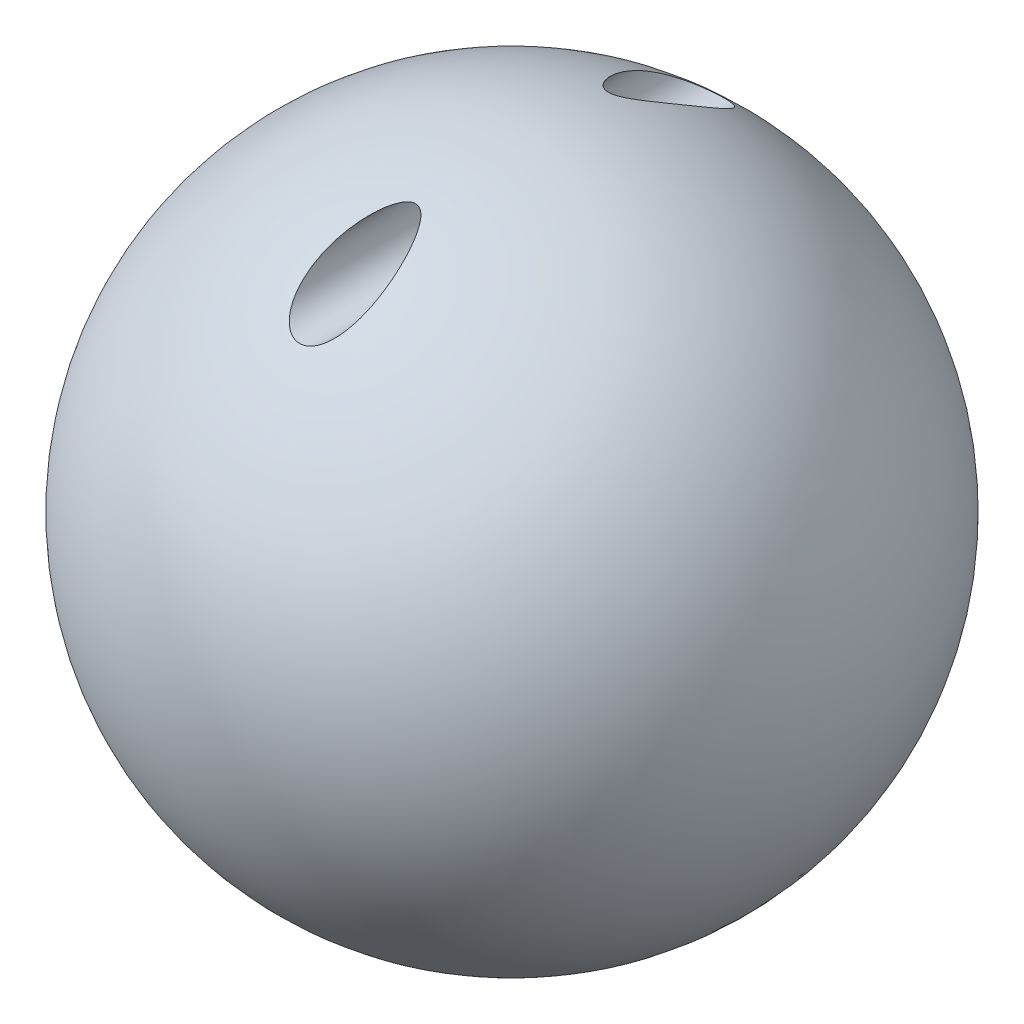
SolidWorks part; units mm, degrees
ref_plane "Front Plane" through (0, 0, 0) normal (0, 0, 1) x (1, 0, 0)
ref_plane "Top Plane" through (0, 0, 0) normal (0, 1, 0) x (1, 0, 0)
ref_plane "Right Plane" through (0, 0, 0) normal (1, 0, 0) x (0, 0, -1)
sketch "Sketch1" plane through (0, 0, 0) normal (0, 0, 1) x (1, 0, 0)
  line L0 (0, 0) -> (0, 50.8)
  arc A0 (0, 50.8) -> (0, 0) centre (0, 25.4) cw
  point P4 (0, 0)
  point P5 (0, 25.4)
  dimension "D1" = 50.8
revolve "Revolve1" add sketch "Sketch1" angle 360 about L0
sketch "Sketch2" plane through (0, 0, 0) normal (0, 0, 1) x (1, 0, 0)
sketch "Sketch4" plane through (0, 0, 0) normal (0, 0, 1) x (1, 0, 0)
  line L0 (0, 0) -> (0, 50.8) construction
  circle A0 centre (0, 47.2578) radius 2.4312
extrude "Cut-Extrude4" cut sketch "Sketch4" against normal through all both and the other way through all
